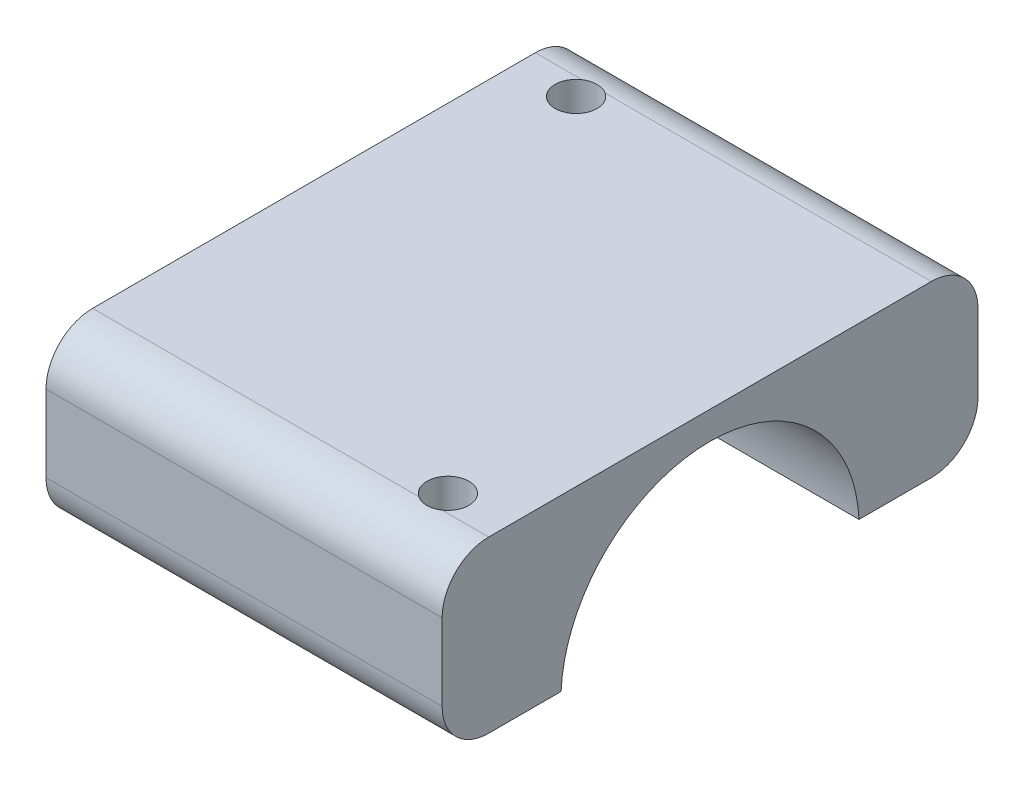
SolidWorks part; units mm, degrees
ref_plane "Front Plane" through (0, 0, 0) normal (0, 0, 1) x (1, 0, 0)
ref_plane "Top Plane" through (0, 0, 0) normal (0, 1, 0) x (1, 0, 0)
ref_plane "Right Plane" through (0, 0, 0) normal (1, 0, 0) x (0, 0, -1)
sketch "Sketch1" plane through (0, 0, 0) normal (1, 0, 0) x (0, 0, -1)
  line L0 (-19, 0.6) -> (19, 0.6)
  line L1 (23, 4.6) -> (23, 11.188)
  line L2 (19, 15.188) -> (-19, 15.188)
  line L3 (-23, 11.188) -> (-23, 4.6)
  arc A0 (19, 0.6) -> (23, 4.6) centre (19, 4.6) ccw
  arc A1 (23, 11.188) -> (19, 15.188) centre (19, 11.188) ccw
  arc A2 (-19, 15.188) -> (-23, 11.188) centre (-19, 11.188) ccw
  arc A3 (-23, 4.6) -> (-19, 0.6) centre (-19, 4.6) ccw
extrude "Boss-Extrude1" add sketch "Sketch1" along normal mid plane 34
sketch "Sketch2" plane through (0, 0, 0) normal (1, 0, 0) x (0, 0, -1)
  circle A0 centre (0, 0) radius 12.8
extrude "Cut-Extrude1" cut sketch "Sketch2" against normal through all and the other way through all
ref_plane "Plane1" through (0, 0.6, 0) normal (0, 1, 0) x (1, 0, 0)
sketch "Sketch3" plane through (0, 0.6, 0) normal (0, 1, 0) x (1, 0, 0)
  circle A0 centre (12, -17.5) radius 1.8
  circle A1 centre (-12, 17.5) radius 1.8
extrude "Cut-Extrude2" cut sketch "Sketch3" along normal blind 15.188
